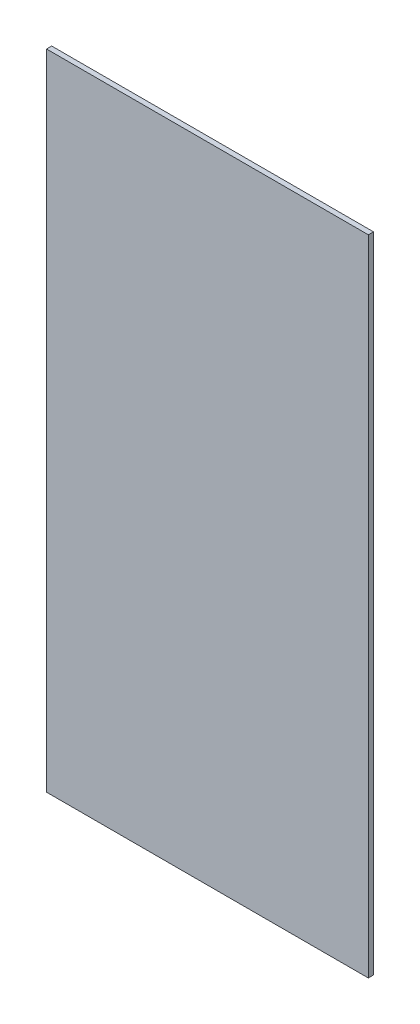
SolidWorks part; units mm, degrees
material "ABS PC"
ref_plane "Front Plane" through (0, 0, 0) normal (0, 0, 1) x (1, 0, 0)
ref_plane "Top Plane" through (0, 0, 0) normal (0, 1, 0) x (1, 0, 0)
ref_plane "Right Plane" through (0, 0, 0) normal (1, 0, 0) x (0, 0, -1)
sketch "Sketch1" plane through (0, 0, 0) normal (0, 0, 1) x (1, 0, 0)
  line L1 (-125, 250) -> (125, 250)
  line L2 (-125, 250) -> (-125, -250)
  line L3 (-125, -250) -> (125, -250)
  line L4 (125, 250) -> (125, -250)
  line L5 (-125, 250) -> (125, -250) construction
  line L6 (-125, -250) -> (125, 250) construction
  point P0 (0, 0)
  dimension "D1" = 250
  dimension "D2" = 500
extrude "Boss-Extrude1" add sketch "Sketch1" along normal blind 4
